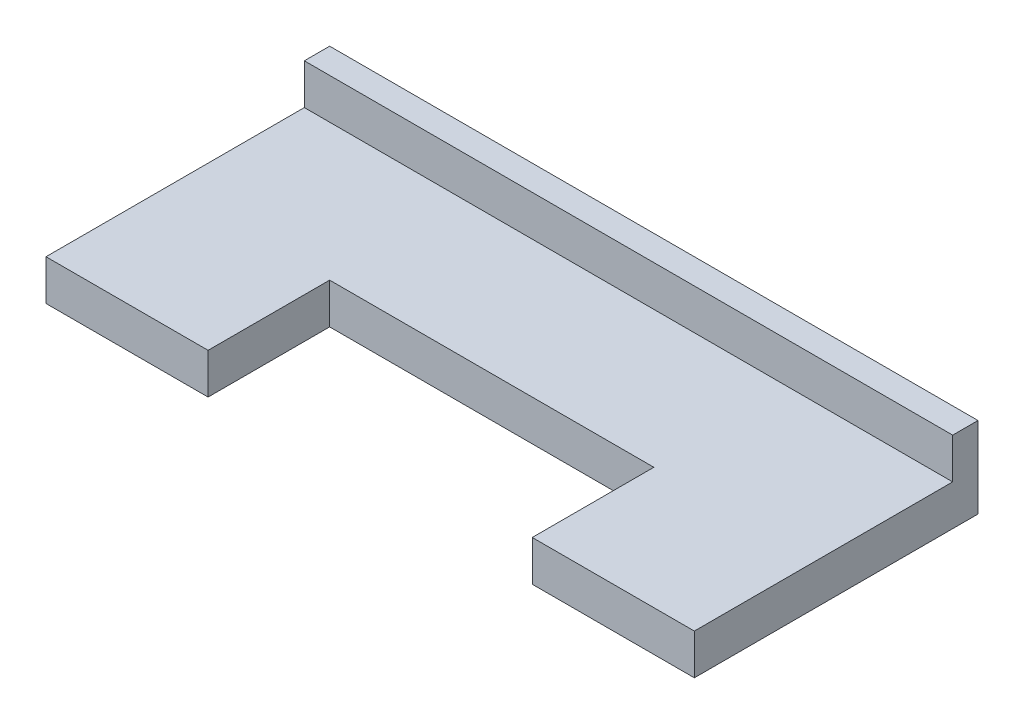
SolidWorks part; units mm, degrees
ref_plane "Front Plane" through (0, 0, 0) normal (0, 0, 1) x (1, 0, 0)
ref_plane "Top Plane" through (0, 0, 0) normal (0, 1, 0) x (1, 0, 0)
ref_plane "Right Plane" through (0, 0, 0) normal (1, 0, 0) x (0, 0, -1)
sketch "Sketch1" plane through (0, 0, 0) normal (0, 1, 0) x (1, 0, 0)
  line L1 (-10.16, -5.08) -> (10.16, -5.08)
  line L2 (-10.16, -5.08) -> (-10.16, 5.08)
  line L3 (-10.16, 5.08) -> (10.16, 5.08)
  line L4 (10.16, -5.08) -> (10.16, 5.08)
  line L5 (-10.16, -5.08) -> (10.16, 5.08) construction
  line L6 (-10.16, 5.08) -> (10.16, -5.08) construction
  point P0 (0, 0)
  dimension "D1" = 20.32
  dimension "D2" = 10.16
extrude "Boss-Extrude1" add sketch "Sketch1" along normal blind 1.27
sketch "Sketch2" plane through (0, 1.27, 0) normal (0, 1, 0) x (1, 0, 0)
  line L0 (-10.16, -5.08) -> (10.16, -5.08) construction
  line L1 (-5.08, -5.08) -> (5.08, -5.08)
  line L2 (-5.08, -5.08) -> (-5.08, 0)
  line L3 (-5.08, 0) -> (5.08, 0)
  line L4 (5.08, -5.08) -> (5.08, 0)
  point P6 (0, 0)
  dimension "D1" = 10.16
extrude "Cut-Extrude1" cut sketch "Sketch2" against normal through all
sketch "Sketch4" plane through (0, 1.27, 0) normal (0, 1, 0) x (1, 0, 0)
  line L0 (10.16, -5.08) -> (10.16, 5.08) construction
  line L1 (-10.16, 5.08) -> (10.16, 5.08)
  line L2 (-10.16, 5.08) -> (-10.16, 4.2862)
  line L3 (-10.16, 4.2862) -> (10.16, 4.2862)
  line L4 (10.16, 5.08) -> (10.16, 4.2862)
  dimension "D1" = 0.7937
extrude "Boss-Extrude2" add sketch "Sketch4" along normal blind 1.27
sketch "Sketch5" plane through (0, 0, 5.08) normal (0, 0, 1) x (1, 0, 0)
  line L0 (10.16, 1.27) -> (5.08, 1.27) construction
  line L1 (5.08, 1.27) -> (5.08, 0) construction
  line L2 (5.08, 0) -> (10.16, 0) construction
  line L3 (10.16, 0) -> (10.16, 1.27) construction
  line L4 (-10.16, 0) -> (-5.08, 0) construction
  line L5 (-5.08, 0) -> (-5.08, 1.27) construction
  line L6 (-5.08, 1.27) -> (-10.16, 1.27) construction
  line L7 (-10.16, 1.27) -> (-10.16, 0) construction
  line L8 (10.16, 1.27) -> (5.08, 1.27)
  line L9 (5.08, 1.27) -> (5.08, 0)
  line L10 (5.08, 0) -> (10.16, 0)
  line L11 (10.16, 0) -> (10.16, 1.27)
  line L12 (-10.16, 0) -> (-5.08, 0)
  line L13 (-5.08, 0) -> (-5.08, 1.27)
  line L14 (-5.08, 1.27) -> (-10.16, 1.27)
  line L15 (-10.16, 1.27) -> (-10.16, 0)
extrude "Cut-Extrude2" cut sketch "Sketch5" against normal blind 1.27
fillet "Fillet1" [suppressed] radius 1.27
